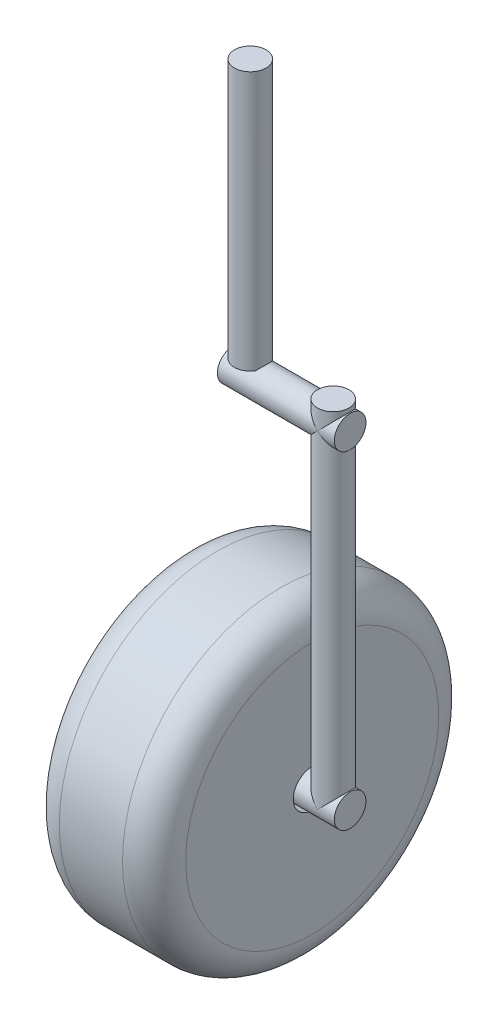
SolidWorks part; units mm, degrees
material "Silicon Rubber"
ref_plane "Front Plane" through (0, 0, 0) normal (0, 0, 1) x (1, 0, 0)
ref_plane "Top Plane" through (0, 0, 0) normal (0, 1, 0) x (1, 0, 0)
ref_plane "Right Plane" through (0, 0, 0) normal (1, 0, 0) x (0, 0, -1)
sketch "Sketch1" plane through (0, 0, 0) normal (1, 0, 0) x (0, 0, -1)
  circle A0 centre (0, 0) radius 5
  circle A1 centre (0, 0) radius 0.6
  dimension "D1" = 10
  dimension "D2" = 1.2
extrude "Boss-Extrude1" add sketch "Sketch1" along normal blind 4
fillet "Fillet1" radius 1 1 edges at (0, 0, -5)
fillet "Fillet2" radius 1 1 edges at (4, 0, -5)
sketch "Sketch2" plane through (0, 0, 0) normal (1, 0, 0) x (0, 0, -1)
  circle A0 centre (0, 0) radius 0.5
  dimension "D1" = 1
extrude "Boss-Extrude2" add sketch "Sketch2" along normal blind 5.2 and the other way blind 0.5 separate body
sketch "Sketch3" plane through (0, 0, 0) normal (0, 1, 0) x (1, 0, 0)
  circle A0 centre (4.6643, 0) radius 0.5
extrude "Boss-Extrude3" add sketch "Sketch3" along normal blind 11
sketch "Sketch5" plane through (0, 0, 0) normal (1, 0, 0) x (0, 0, -1)
  circle A0 centre (0, 10.3729) radius 0.5
extrude "Boss-Extrude4" add sketch "Sketch5" along normal blind 5.2
ref_plane "Plane3" through (0, 16, 0) normal (0, 1, 0) x (1, 0, 0)
sketch "Sketch7" plane through (0, 16, 0) normal (0, 1, 0) x (1, 0, 0)
  circle A0 centre (2.0403, 0) radius 0.5
extrude "Boss-Extrude6" add sketch "Sketch7" along normal blind 3 and the other way blind 5.2
sketch "Sketch8" plane through (0, 0, 0) normal (-1, 0, 0) x (0, 0, 1)
  line L1 (2.2623, 11.8921) -> (-5.4641, 11.8921)
  line L2 (2.2623, 11.8921) -> (2.2623, 7.9949)
  line L3 (2.2623, 7.9949) -> (-5.4641, 7.9949)
  line L4 (-5.4641, 11.8921) -> (-5.4641, 7.9949)
extrude "Cut-Extrude1" cut sketch "Sketch8" against normal blind 1.5
